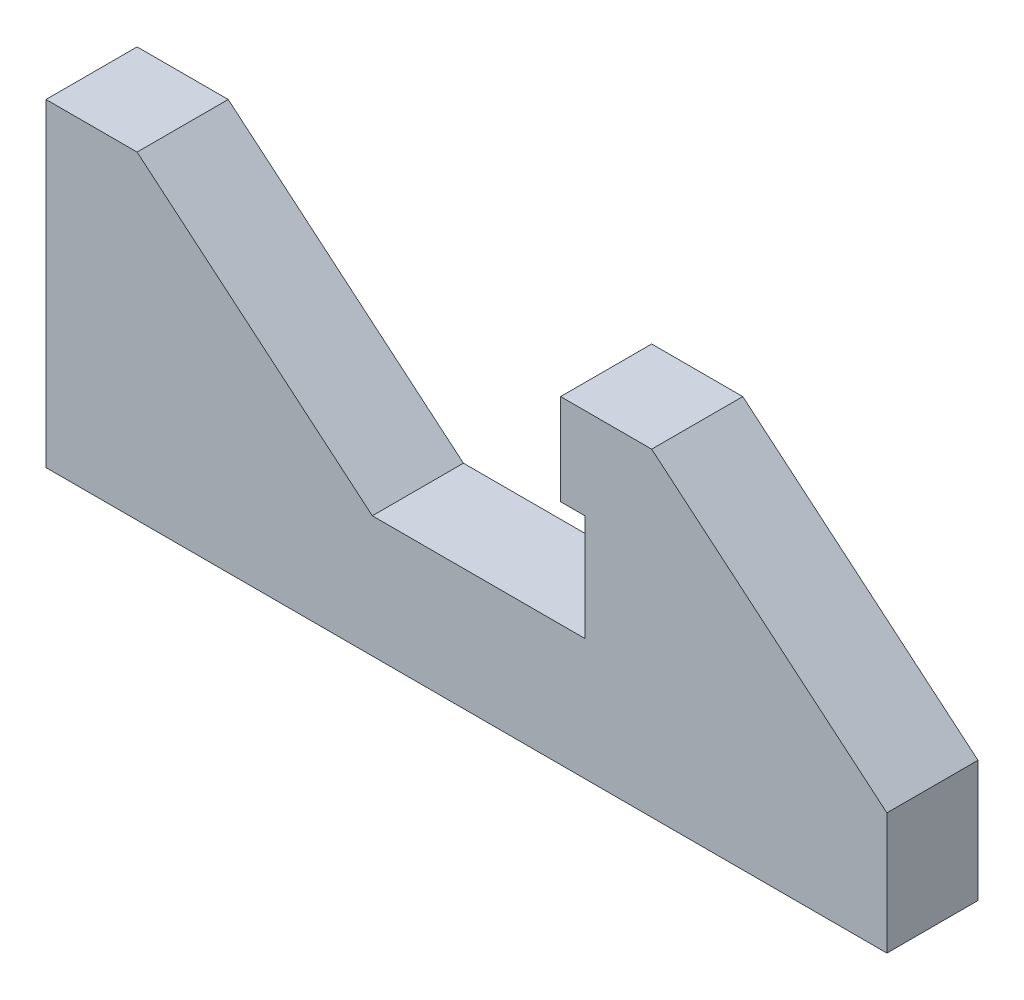
SolidWorks part; units mm, degrees
ref_plane "Front Plane" through (0, 0, 0) normal (0, 0, 1) x (1, 0, 0)
ref_plane "Top Plane" through (0, 0, 0) normal (0, 1, 0) x (1, 0, 0)
ref_plane "Right Plane" through (0, 0, 0) normal (1, 0, 0) x (0, 0, -1)
sketch "Sketch1" plane through (0, 0, 0) normal (0, 0, 1) x (1, 0, 0)
  line L0 (0, 0) -> (0, 105)
  line L1 (0, 105) -> (30, 105)
  line L2 (30, 105) -> (107.464, 40)
  line L3 (107.464, 40) -> (177.464, 40)
  line L4 (177.464, 40) -> (177.464, 75)
  line L5 (177.464, 75) -> (169.464, 75)
  line L6 (169.464, 75) -> (169.464, 105)
  line L7 (169.464, 105) -> (199.464, 105)
  line L8 (199.464, 105) -> (276.928, 40)
  line L9 (276.928, 40) -> (276.928, 0)
  line L10 (276.928, 0) -> (0, 0)
  dimension "D1" = 50
  dimension "D2" = 30
  dimension "D3" = 30
  dimension "D4" = 8
  dimension "D5" = 35
  dimension "D6" = 40
  dimension "D7" = 30
  dimension "D8" = 70
extrude "Boss-Extrude1" add sketch "Sketch1" along normal blind 30
